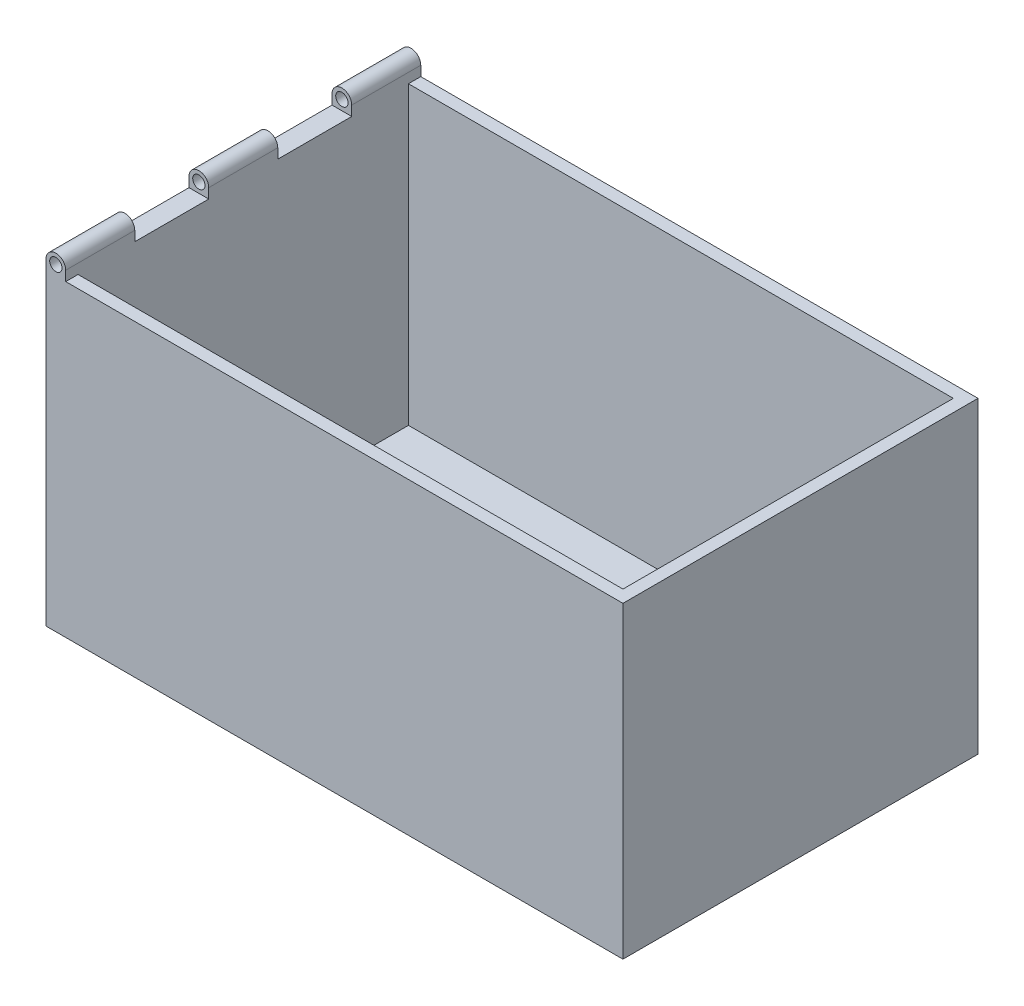
SolidWorks part; units mm, degrees
ref_plane "Front Plane" through (0, 0, 0) normal (0, 0, 1) x (1, 0, 0)
ref_plane "Top Plane" through (0, 0, 0) normal (0, 1, 0) x (1, 0, 0)
ref_plane "Right Plane" through (0, 0, 0) normal (1, 0, 0) x (0, 0, -1)
sketch "Sketch1" plane through (0, 0, 0) normal (0, 1, 0) x (1, 0, 0)
  line L1 (-58.5, 36) -> (58.5, 36)
  line L2 (-58.5, 36) -> (-58.5, -36)
  line L3 (-58.5, -36) -> (58.5, -36)
  line L4 (58.5, 36) -> (58.5, -36)
  point P4 (0, 36)
  point P6 (-58.5, 0)
  dimension "D1" = 117
  dimension "D2" = 72
extrude "Boss-Extrude1" add sketch "Sketch1" against normal blind 2.5
sketch "Sketch2" plane through (0, 0, 0) normal (0, 1, 0) x (1, 0, 0)
  line L1 (-58.5, 36) -> (58.5, 36)
  line L2 (-58.5, 36) -> (-58.5, -36)
  line L3 (-58.5, -36) -> (58.5, -36)
  line L4 (58.5, 36) -> (58.5, -36)
  line L5 (-54.5, 33.5) -> (56, 33.5)
  line L6 (-54.5, 33.5) -> (-54.5, -33.5)
  line L7 (-54.5, -33.5) -> (56, -33.5)
  line L8 (56, 33.5) -> (56, -33.5)
  dimension "D1" = 4
  dimension "D2" = 2.5
  dimension "D3" = 2.5
  dimension "D4" = 2.5
extrude "Boss-Extrude2" add sketch "Sketch2" along normal blind 60
sketch "Sketch3" plane through (0, 0, 0) normal (0, 0, 1) x (1, 0, 0)
  line L0 (-58.5, 62) -> (-58.5, 60)
  line L1 (-58.5, 60) -> (-54.5, 60) construction
  line L2 (-58.5, 60) -> (58.5, 60) construction
  line L3 (-58.5, 60) -> (-54.5, 60)
  line L6 (-54.5, 60) -> (-54.5, 62)
  arc A0 (-58.5, 62) -> (-54.5, 62) centre (-56.5, 62) cw
  circle A1 centre (-56.5, 62) radius 1.25
  point P9 (-56.5, 64)
  dimension "D1" = 4
  dimension "D2" = 2.5
  dimension "D3" = 4
extrude "Boss-Extrude3" add sketch "Sketch3" against normal mid plane 72
sketch "Sketch4" plane through (0, 0, 0) normal (1, 0, 0) x (0, 0, -1)
  line L0 (36, 64) -> (-36, 64) construction
  line L1 (-22, 64) -> (-7, 64)
  line L2 (-22, 64) -> (-22, 60)
  line L3 (-22, 60) -> (-7, 60)
  line L4 (-7, 64) -> (-7, 60)
  line L5 (-36, 60) -> (36, 60) construction
  line L6 (-36, -2.5) -> (-36, 60) construction
  line L7 (7, 64) -> (22, 64)
  line L8 (7, 64) -> (7, 60)
  line L9 (7, 60) -> (22, 60)
  line L10 (22, 64) -> (22, 60)
  line L11 (36, -2.5) -> (36, 60) construction
  dimension "D1" = 14
  dimension "D2" = 14
  dimension "D3" = 14
extrude "Cut-Extrude1" cut sketch "Sketch4" against normal through all both and the other way through all
sketch "Sketch5" plane through (0, 0, 0) normal (0, 1, 0) x (1, 0, 0)
  line L0 (-43.615, 25.5) -> (-17.1257, 25.5) construction
  line L1 (56, 33.5) -> (-54.5, 33.5) construction
  dimension "D1" = 8
sketch "Sketch6" plane through (0, 0, 0) normal (0, 1, 0) x (1, 0, 0)
  line L0 (13.1831, 25.5) -> (13.1831, 14.2303) construction
  line L1 (-43.615, 25.5) -> (-17.1257, 25.5) construction
equation "\"wall\"=2.5"
equation "\"D1@Boss-Extrude1\"=\"wall\""
equation "\"D2@Sketch2\"=\"wall\""
equation "\"D3@Sketch2\"=\"wall\""
equation "\"D4@Sketch2\"=\"wall\""
equation "\"box_width\"=112"
equation "\"D1@Sketch1\"=\"wall\"*2+\"box_width\""
equation "\"box_length\"= 67"
equation "\"D2@Sketch1\"=\"wall\"*2+\"box_length\""
equation "\"axis_hole\"=2.5"
equation "\"D2@Sketch3\"=\"axis_hole\""
equation "\"D1@Boss-Extrude3\"=\"box_length\"+\"wall\"*2"
